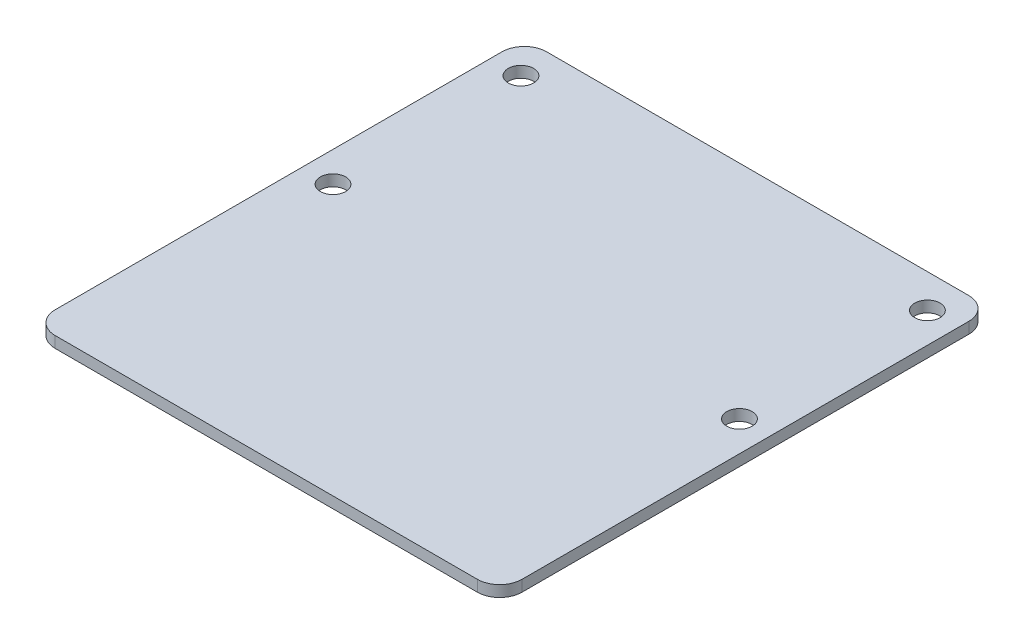
SolidWorks part; units mm, degrees
ref_plane "Plan de face" through (0, 0, 0) normal (0, 0, 1) x (1, 0, 0)
ref_plane "Plan de dessus" through (0, 0, 0) normal (0, 1, 0) x (1, 0, 0)
ref_plane "Plan de droite" through (0, 0, 0) normal (1, 0, 0) x (0, 0, -1)
sketch "Esquisse1" plane through (0, 0, 0) normal (0, 1, 0) x (1, 0, 0)
  line L1 (-31.3, 32.95) -> (31.3, 32.95)
  line L2 (-31.3, 32.95) -> (-31.3, -32.95)
  line L3 (-31.3, -32.95) -> (31.3, -32.95)
  line L4 (31.3, 32.95) -> (31.3, -32.95)
  line L5 (-31.3, 32.95) -> (31.3, -32.95) construction
  line L6 (-31.3, -32.95) -> (31.3, 32.95) construction
  point P0 (0, 0)
  dimension "D1" = 62.6
  dimension "D2" = 65.9
extrude "Boss.-Extru.1" add sketch "Esquisse1" along normal blind 1.5
fillet "Congé1" radius 3 4 edges at (31.3, 0.75, 32.95) (31.3, 0.75, -32.95) (-31.3, 0.75, -32.95) (-31.3, 0.75, 32.95)
sketch "Esquisse2" plane through (0, 1.5, 0) normal (0, 1, 0) x (1, 0, 0)
  line L0 (0, 3.25) -> (0, 0) construction
  line L1 (-27.25, 28.45) -> (27.25, 28.45) construction
  line L2 (-27.25, 28.45) -> (-27.25, 3.25) construction
  line L3 (-27.25, 3.25) -> (27.25, 3.25) construction
  line L4 (27.25, 28.45) -> (27.25, 3.25) construction
  line L5 (28.3, 32.95) -> (-28.3, 32.95) construction
  circle A0 centre (-27.25, 28.45) radius 1.7
  circle A1 centre (-27.25, 3.25) radius 1.7
  circle A2 centre (27.25, 28.45) radius 1.7
  circle A3 centre (27.25, 3.25) radius 1.7
  dimension "D4" = 3.4
  dimension "D1" = 25.2
  dimension "D2" = 54.5
  dimension "D3" = 4.5
extrude "Enlèv. mat.-Extru.1" cut sketch "Esquisse2" against normal through all
